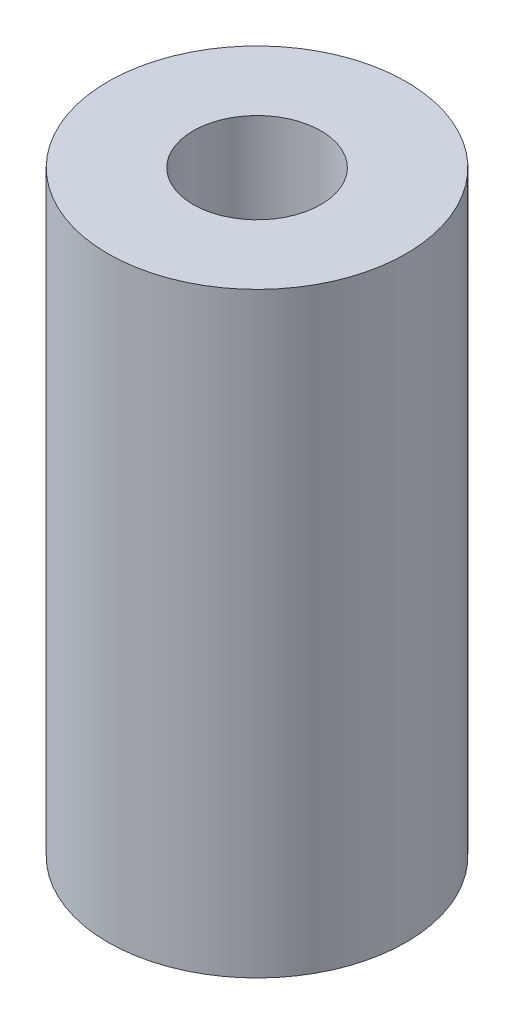
SolidWorks part; units mm, degrees
ref_plane "Front Plane" through (0, 0, 0) normal (0, 0, 1) x (1, 0, 0)
ref_plane "Top Plane" through (0, 0, 0) normal (0, 1, 0) x (1, 0, 0)
ref_plane "Right Plane" through (0, 0, 0) normal (1, 0, 0) x (0, 0, -1)
sketch "Sketch1" plane through (0, 0, 0) normal (0, 1, 0) x (1, 0, 0)
  circle A0 centre (0, 0) radius 1.5
  circle A1 centre (0, 0) radius 3.5
  dimension "D1" = 3
  dimension "D2" = 7
extrude "Boss-Extrude1" add sketch "Sketch1" along normal blind 14
